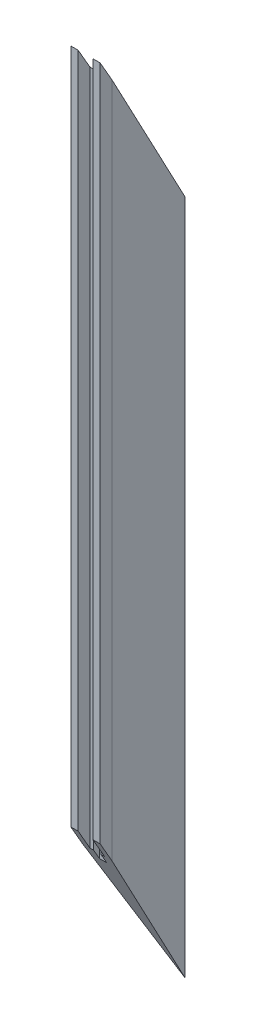
SolidWorks part; units mm, degrees
material "1023 Carbon Steel Sheet (SS)"
ref_plane "Front Plane" through (0, 0, 0) normal (0, 0, 1) x (1, 0, 0)
ref_plane "Top Plane" through (0, 0, 0) normal (0, 1, 0) x (1, 0, 0)
ref_plane "Right Plane" through (0, 0, 0) normal (1, 0, 0) x (0, 0, -1)
sketch "Sketch1" plane through (0, 0, 0) normal (0, 1, 0) x (1, 0, 0)
  line L0 (0, 0) -> (0, 38.1) construction
  line L1 (0, 38.1) -> (-6.35, 0)
  line L2 (0, 38.1) -> (6.35, 0)
  line L3 (0, 18.7872) -> (3.2182, -0.522) construction
  line L4 (0, 18.7872) -> (-3.2182, -0.522) construction
  line L5 (0, 0) -> (3.175, 0) construction
  line L6 (0, 0) -> (-3.175, 0) construction
  line L7 (-3.175, 0) -> (-3.175, -5.08)
  line L8 (-3.175, -5.08) -> (-6.35, -5.08)
  line L9 (-6.35, -5.08) -> (-6.35, 0)
  line L10 (3.175, 0) -> (3.175, -5.08)
  line L11 (3.175, -5.08) -> (6.35, -5.08)
  line L12 (6.35, -5.08) -> (6.35, 0)
  line L13 (-3.175, 0) -> (-1.5875, 0)
  line L19 (-1.5875, 0) -> (-1.5875, 2.54)
  line L20 (-1.5875, 2.54) -> (1.5875, 2.54)
  line L21 (1.5875, 2.54) -> (1.5875, 0)
  line L22 (1.5875, 0) -> (3.175, 0)
  dimension "D7" = 1.5875
  dimension "D1" = 38.1
  dimension "D2" = 6.35
  dimension "D3" = 6.35
  dimension "D5" = 3.175
  dimension "D6" = 3.175
  dimension "D8" = 5.08
  dimension "D9" = 5.08
  dimension "D10" = 1.5875
  dimension "D11" = 3.175
  dimension "D12" = 2.54
  dimension "D4" = 3.175
extrude "Boss-Extrude1" add sketch "Sketch1" along normal blind 369.316
sketch "Sketch2" plane through (-6.35, 0, 0) normal (-1, 0, 0) x (0, 0, 1)
  line L0 (5.08, 369.316) -> (-38.1, 294.2237)
  line L1 (-38.1, 369.316) -> (-38.1, 0) construction
  line L2 (5.08, 369.316) -> (5.08, 0) construction
  line L3 (-38.1, 294.2237) -> (-38.1, 369.316)
  line L4 (-38.1, 369.316) -> (5.08, 369.316)
  dimension "D1" = 29.9
extrude "Cut-Extrude1" cut sketch "Sketch2" against normal blind 17.526
sketch "Sketch3" plane through (-6.35, 0, 0) normal (-1, 0, 0) x (0, 0, 1)
  line L0 (5.08, 76.2) -> (-38.1, 1.1077)
  line L1 (5.08, 369.316) -> (5.08, 0) construction
  line L2 (-38.1, 1.1077) -> (-38.1, 0)
  line L3 (-38.1, 0) -> (5.08, 0)
  line L4 (5.08, 0) -> (5.08, 76.2)
  dimension "D1" = 150.1
  dimension "D2" = 293.116
extrude "Cut-Extrude2" cut sketch "Sketch3" against normal blind 17.526
